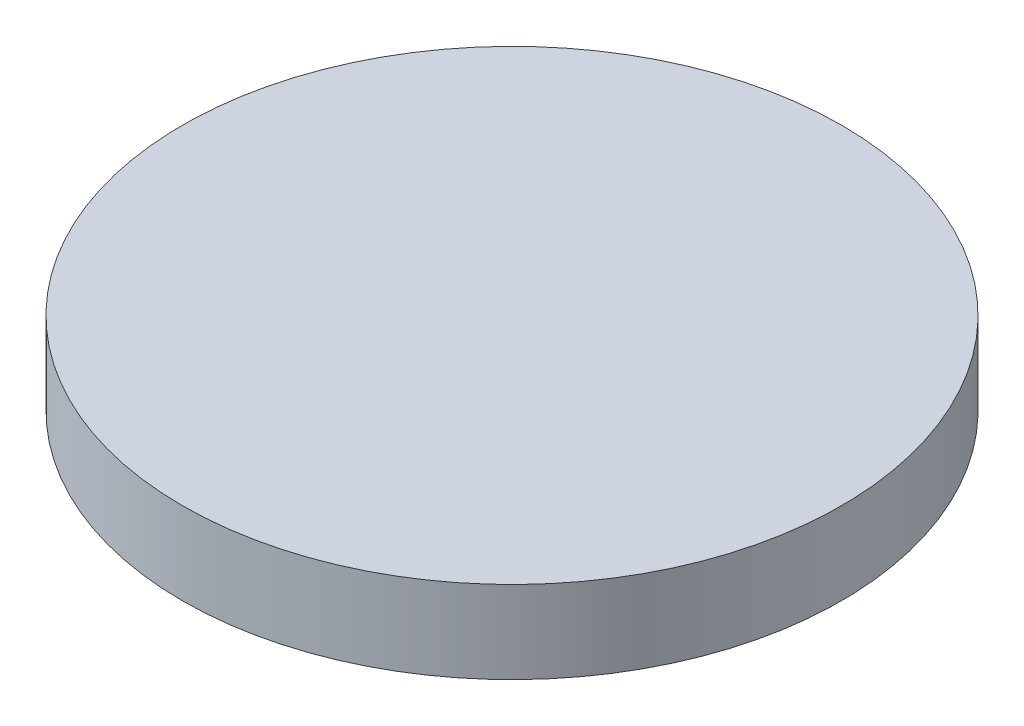
SolidWorks part; units mm, degrees
ref_plane "Front Plane" through (0, 0, 0) normal (0, 0, 1) x (1, 0, 0)
ref_plane "Top Plane" through (0, 0, 0) normal (0, 1, 0) x (1, 0, 0)
ref_plane "Right Plane" through (0, 0, 0) normal (1, 0, 0) x (0, 0, -1)
sketch "Sketch1" plane through (0, 0, 0) normal (0, 1, 0) x (1, 0, 0)
  circle A0 centre (0, 0) radius 12
  dimension "D1" = 24
extrude "Boss-Extrude1" add sketch "Sketch1" along normal blind 3
